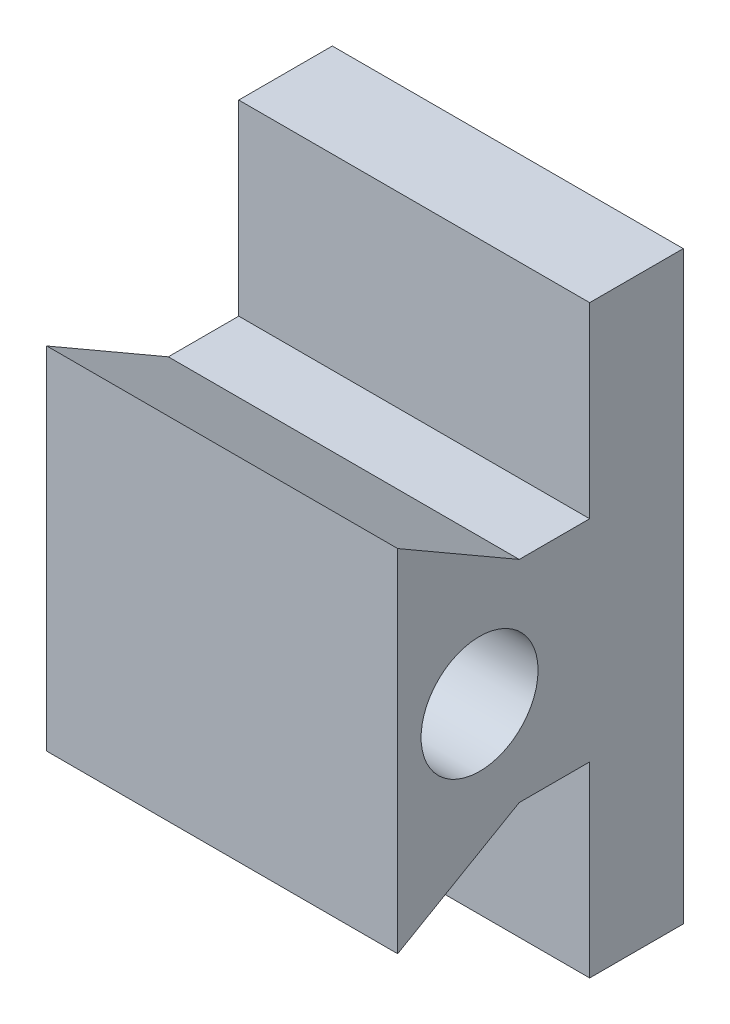
SolidWorks part; units mm, degrees
material "Polyetheretherketone (PEEK)"
ref_plane "Front Plane" through (0, 0, 0) normal (0, 0, 1) x (1, 0, 0)
ref_plane "Top Plane" through (0, 0, 0) normal (0, 1, 0) x (1, 0, 0)
ref_plane "Right Plane" through (0, 0, 0) normal (1, 0, 0) x (0, 0, -1)
sketch "Sketch1" plane through (0, 0, 0) normal (1, 0, 0) x (0, 0, -1)
  line L0 (0, -1.5) -> (0, 1.5)
  line L1 (0, 1.5) -> (1.0392, 0.9)
  line L2 (1.0392, -0.9) -> (1.6413, -0.9)
  line L3 (1.6413, 2.5) -> (2.4413, 2.5)
  line L4 (2.4413, 2.5) -> (2.4413, -2.5)
  line L5 (2.4413, -2.5) -> (1.6413, -2.5)
  line L6 (1.6413, -0.9) -> (1.6413, -2.5)
  line L7 (1.0392, -0.9) -> (0, -1.5)
  line L8 (1.0392, 0.9) -> (1.6413, 0.9)
  line L9 (1.6413, 0.9) -> (1.6413, 2.5)
  point P4 (0, 0)
  point P12 (2.4413, 0)
  dimension "D1" = 3
  dimension "D2" = 60
  dimension "D3" = 60
  dimension "D4" = 5
  dimension "D5" = 0.8
  dimension "D6" = 0.6021
  dimension "D7" = 1.8
extrude "Boss-Extrude1" add sketch "Sketch1" along normal blind 3
sketch "Sketch2" plane through (3, 0, 0) normal (1, 0, 0) x (0, 0, -1)
  circle A0 centre (0.7, 0) radius 0.5
  dimension "D1" = 1
  dimension "D2" = 0.7
extrude "Cut-Extrude1" cut sketch "Sketch2" against normal through all
